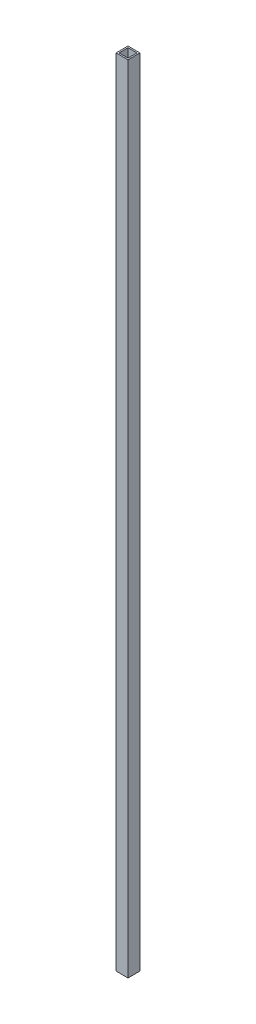
SolidWorks part; units mm, degrees
material "6061 Alloy"
ref_plane "Front Plane" through (0, 0, 0) normal (0, 0, 1) x (1, 0, 0)
ref_plane "Top Plane" through (0, 0, 0) normal (0, 1, 0) x (1, 0, 0)
ref_plane "Right Plane" through (0, 0, 0) normal (1, 0, 0) x (0, 0, -1)
sketch "Sketch1" plane through (0, 0, 0) normal (0, 1, 0) x (1, 0, 0)
  line L1 (4.7625, 4.7625) -> (-4.7625, 4.7625)
  line L2 (4.7625, 4.7625) -> (4.7625, -4.7625)
  line L3 (4.7625, -4.7625) -> (-4.7625, -4.7625)
  line L4 (-4.7625, 4.7625) -> (-4.7625, -4.7625)
  line L5 (0, -4.7625) -> (0, 4.7625) construction
  line L6 (4.7625, 0) -> (-4.7625, 0) construction
  line L7 (6.35, 6.35) -> (-6.35, 6.35)
  line L8 (6.35, 6.35) -> (6.35, -6.35)
  line L9 (6.35, -6.35) -> (-6.35, -6.35)
  line L10 (-6.35, 6.35) -> (-6.35, -6.35)
  line L11 (0, -6.35) -> (0, 6.35) construction
  line L12 (6.35, 0) -> (-6.35, 0) construction
  point P0 (0, 0)
  point P4 (0, 0)
  dimension "D1" = 12.7
  dimension "D2" = 1.5875
extrude "Boss-Extrude1" add sketch "Sketch1" along normal blind 845
